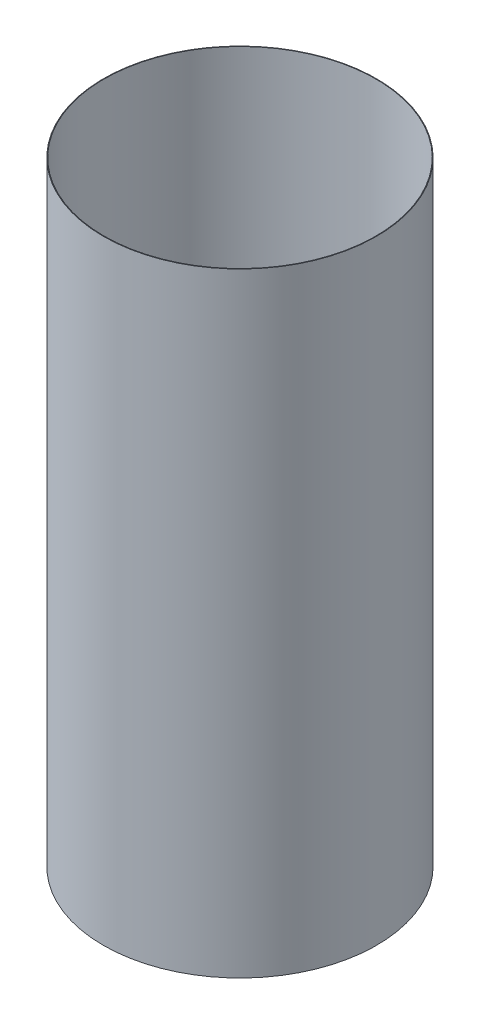
SolidWorks part; units mm, degrees
ref_plane "Front Plane" through (0, 0, 0) normal (0, 0, 1) x (1, 0, 0)
ref_plane "Top Plane" through (0, 0, 0) normal (0, 1, 0) x (1, 0, 0)
ref_plane "Right Plane" through (0, 0, 0) normal (1, 0, 0) x (0, 0, -1)
sketch "Sketch1" plane through (0, 0, 0) normal (0, 1, 0) x (1, 0, 0)
  circle A0 centre (0, 0) radius 28.956
  circle A1 centre (0, 0) radius 28.829
  dimension "D1" = 57.912
  dimension "D2" = 0.127
extrude "Boss-Extrude1" add sketch "Sketch1" along normal blind 130.175
